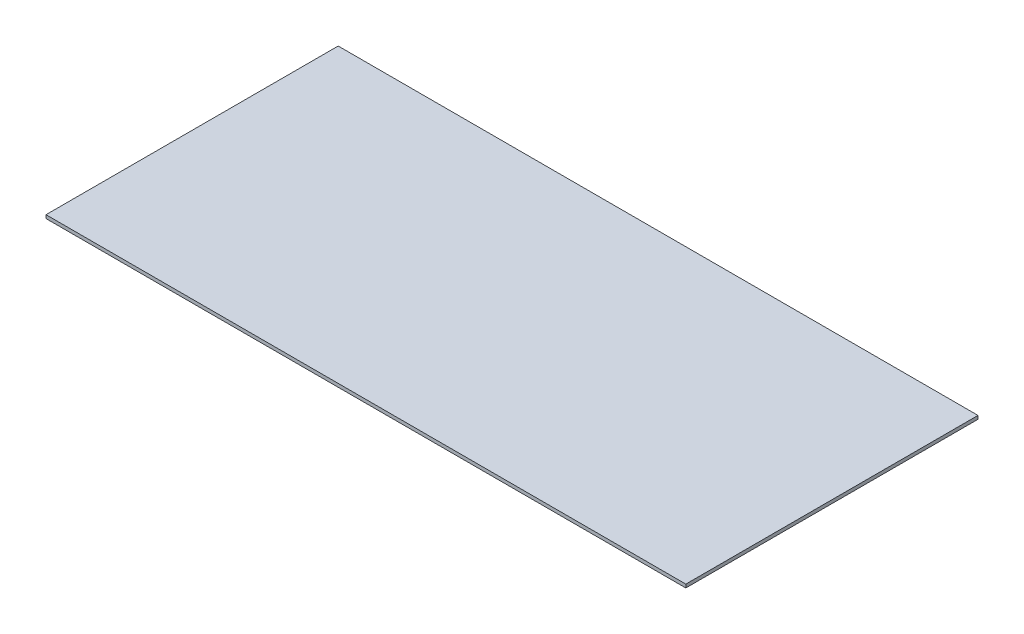
SolidWorks part; units mm, degrees
material "PVC 0.007 Plasticized"
ref_plane "Front Plane" through (0, 0, 0) normal (0, 0, 1) x (1, 0, 0)
ref_plane "Top Plane" through (0, 0, 0) normal (0, 1, 0) x (1, 0, 0)
ref_plane "Right Plane" through (0, 0, 0) normal (1, 0, 0) x (0, 0, -1)
sketch "Sketch2" plane through (0, 0, 0) normal (0, 1, 0) x (1, 0, 0)
  line L1 (-9955.5238, 4166.9048) -> (-9009.5238, 4166.9048)
  line L2 (-9955.5238, 4166.9048) -> (-9955.5238, 3734.9048)
  line L3 (-9955.5238, 3734.9048) -> (-9009.5238, 3734.9048)
  line L4 (-9009.5238, 4166.9048) -> (-9009.5238, 3734.9048)
  dimension "D1" = 946
  dimension "D2" = 432
extrude "Boss-Extrude1" add sketch "Sketch2" along normal blind 5
